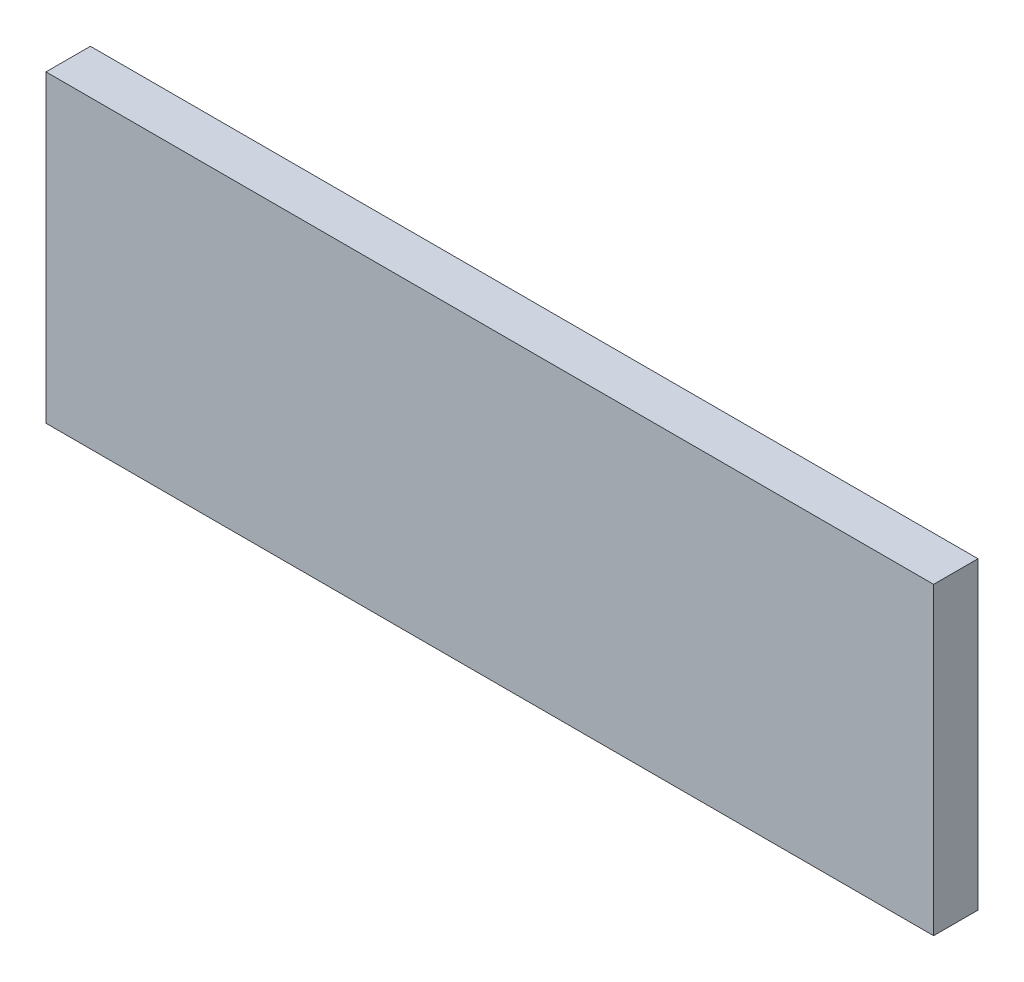
SolidWorks part; units mm, degrees
ref_plane "Ön Düzlem" through (0, 0, 0) normal (0, 0, 1) x (1, 0, 0)
ref_plane "Üst Düzlem" through (0, 0, 0) normal (0, 1, 0) x (1, 0, 0)
ref_plane "Sağ Düzlem" through (0, 0, 0) normal (1, 0, 0) x (0, 0, -1)
sketch "Çizim1" plane through (0, 0, 0) normal (0, 0, 1) x (1, 0, 0)
  line L1 (0, 0) -> (35, 0)
  line L2 (0, 0) -> (0, 12)
  line L3 (0, 12) -> (35, 12)
  line L4 (35, 0) -> (35, 12)
  dimension "D1" = 12
  dimension "D2" = 35
extrude "Yükseklik-Ekstrüzyon1" add sketch "Çizim1" along normal blind 1.75
